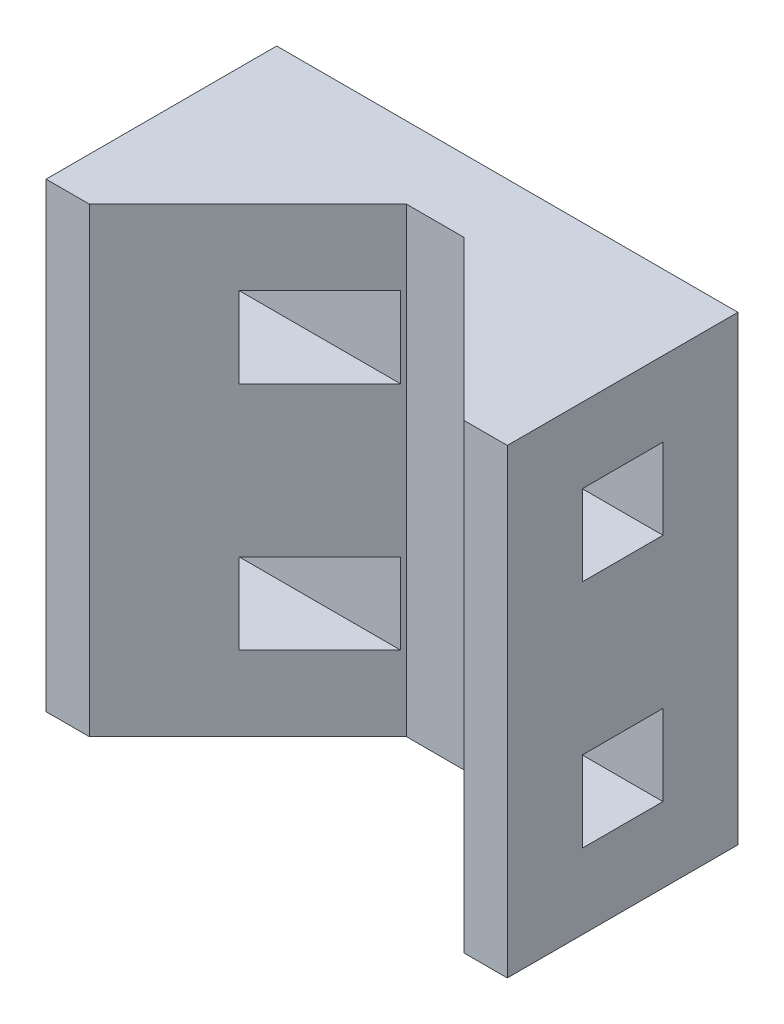
SolidWorks part; units mm, degrees
ref_plane "Plano frontal" through (0, 0, 0) normal (0, 0, 1) x (1, 0, 0)
ref_plane "Plano superior" through (0, 0, 0) normal (0, 1, 0) x (1, 0, 0)
ref_plane "Plano direito" through (0, 0, 0) normal (1, 0, 0) x (0, 0, -1)
sketch "Esboço1" plane through (0, 0, 0) normal (0, 0, 1) x (1, 0, 0)
  line L0 (-25, 0) -> (25, 0)
  line L1 (25, 0) -> (25, 8)
  line L2 (25, 8) -> (23.5, 8)
  line L3 (23.5, 8) -> (18, 2.5)
  line L4 (18, 2.5) -> (-18, 2.5)
  line L5 (0, 0) -> (0, 2.5) construction
  line L6 (-23.5, 8) -> (-18, 2.5)
  line L7 (-25, 8) -> (-23.5, 8)
  line L8 (-25, 0) -> (-25, 8)
  dimension "D1" = 45
  dimension "D2" = 2.5
  dimension "D3" = 1.5
  dimension "D4" = 8
extrude "Ressalto-extrusão1" add sketch "Esboço1" along normal blind 16
sketch "Esboço2" plane through (25, 0, 0) normal (1, 0, 0) x (0, 0, -1)
  line L0 (-8, 0) -> (-8, 4) construction
  line L1 (-16, 0) -> (0, 0) construction
  line L2 (-8, 4) -> (-4, 4) construction
  line L3 (-8, 4) -> (-12, 4) construction
  line L4 (-5.4, 5.4) -> (-5.4, 2.6)
  line L5 (-13.4, 5.4) -> (-10.6, 5.4)
  line L6 (-13.4, 5.4) -> (-13.4, 2.6)
  line L7 (-13.4, 2.6) -> (-10.6, 2.6)
  line L8 (-10.6, 5.4) -> (-10.6, 2.6)
  line L9 (-13.4, 5.4) -> (-10.6, 2.6) construction
  line L10 (-13.4, 2.6) -> (-10.6, 5.4) construction
  line L11 (-5.4, 5.4) -> (-2.6, 5.4)
  line L12 (-5.4, 5.4) -> (-2.6, 2.6) construction
  line L13 (-5.4, 2.6) -> (-2.6, 2.6)
  line L14 (-2.6, 5.4) -> (-2.6, 2.6)
  line L15 (-5.4, 2.6) -> (-2.6, 5.4) construction
extrude "Corte-extrusão1" cut sketch "Esboço2" against normal through all
sketch "Esboço3" plane through (0, 2.5, 0) normal (0, 1, 0) x (1, 0, 0)
  line L0 (0, 0) -> (0, -16) construction
  line L1 (18, -16) -> (-18, -16) construction
  line L3 (-14, -3) -> (14, -3)
  line L4 (-14, -3) -> (-14, -13)
  line L5 (-14, -13) -> (14, -13)
  line L6 (14, -3) -> (14, -13)
  line L7 (-14, -3) -> (14, -13) construction
  line L8 (-14, -13) -> (14, -3) construction
  point P5 (0, -8)
sketch "Esboço4" plane through (0, 2.5, 0) normal (0, 1, 0) x (1, 0, 0)
  line L0 (0, -8) -> (-16, -8) construction
  line L1 (-16, -8) -> (-16, -4) construction
  line L2 (-9.4, -2.6) -> (-6.6, -5.4) construction
  line L3 (-17.4, -2.6) -> (-14.6, -2.6)
  line L4 (-17.4, -2.6) -> (-17.4, -5.4)
  line L5 (-17.4, -5.4) -> (-14.6, -5.4)
  line L6 (-14.6, -2.6) -> (-14.6, -5.4)
  line L7 (-17.4, -2.6) -> (-14.6, -5.4) construction
  line L8 (-17.4, -5.4) -> (-14.6, -2.6) construction
  line L9 (-9.4, -5.4) -> (-6.6, -2.6) construction
  line L10 (-9.4, -2.6) -> (-9.4, -5.4)
  line L11 (-9.4, -2.6) -> (-6.6, -2.6)
  line L12 (-6.6, -2.6) -> (-6.6, -5.4)
  line L13 (-9.4, -5.4) -> (-6.6, -5.4)
  line L14 (-1.4, -2.6) -> (1.4, -5.4) construction
  line L15 (-1.4, -5.4) -> (1.4, -2.6) construction
  line L16 (-1.4, -2.6) -> (-1.4, -5.4)
  line L17 (-1.4, -2.6) -> (1.4, -2.6)
  line L18 (1.4, -2.6) -> (1.4, -5.4)
  line L19 (-1.4, -5.4) -> (1.4, -5.4)
  line L20 (6.6, -2.6) -> (9.4, -5.4) construction
  line L21 (6.6, -5.4) -> (9.4, -2.6) construction
  line L22 (6.6, -2.6) -> (6.6, -5.4)
  line L23 (6.6, -2.6) -> (9.4, -2.6)
  line L24 (9.4, -2.6) -> (9.4, -5.4)
  line L25 (6.6, -5.4) -> (9.4, -5.4)
  line L26 (14.6, -2.6) -> (17.4, -5.4) construction
  line L27 (14.6, -5.4) -> (17.4, -2.6) construction
  line L28 (14.6, -2.6) -> (14.6, -5.4)
  line L29 (14.6, -2.6) -> (17.4, -2.6)
  line L30 (17.4, -2.6) -> (17.4, -5.4)
  line L31 (14.6, -5.4) -> (17.4, -5.4)
  line L32 (-9.4, -10.6) -> (-6.6, -13.4) construction
  line L33 (-9.4, -13.4) -> (-6.6, -10.6) construction
  line L34 (-9.4, -10.6) -> (-9.4, -13.4)
  line L35 (-9.4, -10.6) -> (-6.6, -10.6)
  line L36 (-6.6, -10.6) -> (-6.6, -13.4)
  line L37 (-9.4, -13.4) -> (-6.6, -13.4)
  line L38 (-1.4, -10.6) -> (1.4, -13.4) construction
  line L39 (-1.4, -13.4) -> (1.4, -10.6) construction
  line L40 (-1.4, -10.6) -> (-1.4, -13.4)
  line L41 (-1.4, -10.6) -> (1.4, -10.6)
  line L42 (1.4, -10.6) -> (1.4, -13.4)
  line L43 (-1.4, -13.4) -> (1.4, -13.4)
  line L44 (6.6, -10.6) -> (9.4, -13.4) construction
  line L45 (6.6, -13.4) -> (9.4, -10.6) construction
  line L46 (6.6, -10.6) -> (6.6, -13.4)
  line L47 (6.6, -10.6) -> (9.4, -10.6)
  line L48 (9.4, -10.6) -> (9.4, -13.4)
  line L49 (6.6, -13.4) -> (9.4, -13.4)
  line L50 (14.6, -10.6) -> (17.4, -13.4) construction
  line L51 (14.6, -13.4) -> (17.4, -10.6) construction
  line L52 (14.6, -10.6) -> (14.6, -13.4)
  line L53 (14.6, -10.6) -> (17.4, -10.6)
  line L54 (17.4, -10.6) -> (17.4, -13.4)
  line L55 (14.6, -13.4) -> (17.4, -13.4)
  line L56 (-17.4, -10.6) -> (-14.6, -13.4) construction
  line L57 (-17.4, -13.4) -> (-14.6, -10.6) construction
  line L58 (-17.4, -10.6) -> (-17.4, -13.4)
  line L59 (-17.4, -10.6) -> (-14.6, -10.6)
  line L60 (-14.6, -10.6) -> (-14.6, -13.4)
  line L61 (-17.4, -13.4) -> (-14.6, -13.4)
  dimension "D1" = 5
  dimension "D2" = 2
extrude "Corte-extrusão2" cut sketch "Esboço4" against normal through all
move or copy body "Corpo-Mover/Copiar1" bodies to move or copy 104 copy no rotation origin (0, 4, 8) rotation axis (1, 0, 0) rotation angle 90
sketch "Esboço6" plane through (0, 0, 4) normal (0, 0, -1) x (-1, 0, 0)
  line L1 (25, -4) -> (-25, -4) construction
  line L2 (5, -4) -> (5, 12)
  line L3 (25, 12) -> (-25, 12) construction
  line L4 (5, 12) -> (-25, 12)
  line L5 (-25, 12) -> (-25, -4)
  line L6 (5, -4) -> (-25, -4)
extrude "Corte-extrusão3" cut sketch "Esboço6" against normal through all
mirror "Espelhar3" about plane through (-5, -4, 12) normal (-1, 0, 0) of bodies 106
sketch "Esboço7" plane through (0, 0, 6.5) normal (0, 0, 1) x (1, 0, 0)
  line L1 (-17.582, 9.9145) -> (7.6394, 9.9145)
  line L2 (-17.582, 9.9145) -> (-17.582, -2.6616)
  line L3 (-17.582, -2.6616) -> (7.6394, -2.6616)
  line L4 (7.6394, 9.9145) -> (7.6394, -2.6616)
extrude "Ressalto-extrusão2" add sketch "Esboço7" against normal through all
sketch "Esboço8" plane through (0, 0, 6.5) normal (0, 0, 1) x (1, 0, 0)
  line L0 (-5, -4) -> (-5, 12) construction
  line L1 (8, -4) -> (-18, -4) construction
  line L2 (8, 12) -> (-18, 12) construction
  line L3 (-5, 4) -> (-5, 8) construction
  line L4 (-5, 8) -> (-13, 8) construction
  line L5 (-6.4, 9.4) -> (-3.6, 9.4)
  line L6 (-14.4, 9.4) -> (-11.6, 9.4)
  line L7 (-14.4, 9.4) -> (-14.4, 6.6)
  line L8 (-14.4, 6.6) -> (-11.6, 6.6)
  line L9 (-11.6, 9.4) -> (-11.6, 6.6)
  line L10 (-14.4, 9.4) -> (-11.6, 6.6) construction
  line L11 (-14.4, 6.6) -> (-11.6, 9.4) construction
  line L12 (-6.4, 9.4) -> (-6.4, 6.6)
  line L13 (-6.4, 6.6) -> (-3.6, 6.6)
  line L14 (-3.6, 9.4) -> (-3.6, 6.6)
  line L15 (-6.4, 9.4) -> (-3.6, 6.6) construction
  line L16 (-6.4, 6.6) -> (-3.6, 9.4) construction
  line L17 (1.6, 9.4) -> (4.4, 9.4)
  line L18 (1.6, 9.4) -> (1.6, 6.6)
  line L19 (1.6, 6.6) -> (4.4, 6.6)
  line L20 (4.4, 9.4) -> (4.4, 6.6)
  line L21 (1.6, 9.4) -> (4.4, 6.6) construction
  line L22 (1.6, 6.6) -> (4.4, 9.4) construction
  line L23 (-6.4, 1.4) -> (-3.6, 1.4)
  line L24 (-6.4, 1.4) -> (-6.4, -1.4)
  line L25 (-6.4, -1.4) -> (-3.6, -1.4)
  line L26 (-3.6, 1.4) -> (-3.6, -1.4)
  line L27 (-6.4, 1.4) -> (-3.6, -1.4) construction
  line L28 (-6.4, -1.4) -> (-3.6, 1.4) construction
  line L29 (1.6, 1.4) -> (4.4, 1.4)
  line L30 (1.6, 1.4) -> (1.6, -1.4)
  line L31 (1.6, -1.4) -> (4.4, -1.4)
  line L32 (4.4, 1.4) -> (4.4, -1.4)
  line L33 (1.6, 1.4) -> (4.4, -1.4) construction
  line L34 (1.6, -1.4) -> (4.4, 1.4) construction
  line L35 (-14.4, 1.4) -> (-11.6, 1.4)
  line L36 (-14.4, 1.4) -> (-14.4, -1.4)
  line L37 (-14.4, -1.4) -> (-11.6, -1.4)
  line L38 (-11.6, 1.4) -> (-11.6, -1.4)
  line L39 (-14.4, 1.4) -> (-11.6, -1.4) construction
  line L40 (-14.4, -1.4) -> (-11.6, 1.4) construction
  dimension "D1" = 4
  dimension "D2" = 8
  dimension "D3" = 2.8
  dimension "D4" = 3
  dimension "D5" = 2
extrude "Corte-extrusão4" cut sketch "Esboço8" against normal through all
sketch "Esboço10" plane through (0, 0, 4) normal (0, 0, -1) x (-1, 0, 0)
  line L1 (25, -4) -> (-15, -4) construction
  line L2 (17, -4) -> (17, 12)
  line L3 (25, 12) -> (-15, 12) construction
  line L4 (17, 12) -> (-15, 12)
  line L5 (-15, 12) -> (-15, -4)
  line L6 (-15, -4) -> (17, -4)
extrude "Corte-extrusão5" cut sketch "Esboço10" against normal blind 10
mirror "Espelhar4" about plane through (-17, -4, 14) normal (-1, 0, 0) of bodies 112
